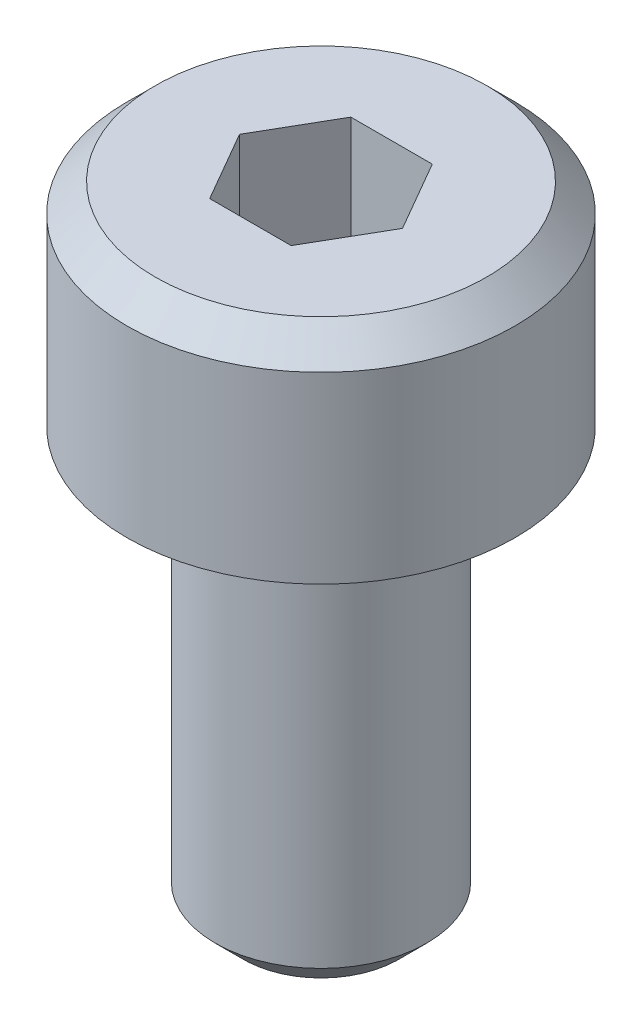
SolidWorks part; units mm, degrees
ref_plane "Front Plane" through (0, 0, 0) normal (0, 0, 1) x (1, 0, 0)
ref_plane "Top Plane" through (0, 0, 0) normal (0, 1, 0) x (1, 0, 0)
ref_plane "Right Plane" through (0, 0, 0) normal (1, 0, 0) x (0, 0, -1)
sketch "Sketch2" plane through (0, 0, 0) normal (0, 0, 1) x (1, 0, 0)
  line L0 (0, 0) -> (0, 25) construction
  line L1 (0, 9) -> (2.75, 9)
  line L2 (2.75, 9) -> (2.75, 6)
  line L3 (2.75, 6) -> (1.5, 6)
  line L4 (1.5, 6) -> (1.5, 0)
  line L5 (1.5, 0) -> (0, 0)
  line L6 (0, 0) -> (0, 9)
  dimension "D1" = 3
  dimension "D2" = 5.5
  dimension "D3" = 3
  dimension "D4" = 9
revolve "Revolve1" add sketch "Sketch2" angle 360 about L0
chamfer "Chamfer1" distance 0.4 angle 45 2 edges at (0, 9, -2.75) (0, 0, -1.5)
sketch "Sketch4" plane through (0, 9, 0) normal (0, 1, 0) x (1, 0, 0)
  line L1 (1.1547, 0) -> (0.5774, 1)
  line L2 (0.5774, 1) -> (-0.5774, 1)
  line L3 (-0.5774, 1) -> (-1.1547, 0)
  line L4 (-1.1547, 0) -> (-0.5774, -1)
  line L5 (-0.5774, -1) -> (0.5774, -1)
  line L6 (0.5774, -1) -> (1.1547, 0)
  circle A0 centre (0, 0) radius 1 construction
  dimension "D1" = 2
extrude "Cut-Extrude2" cut sketch "Sketch4" against normal blind 4
